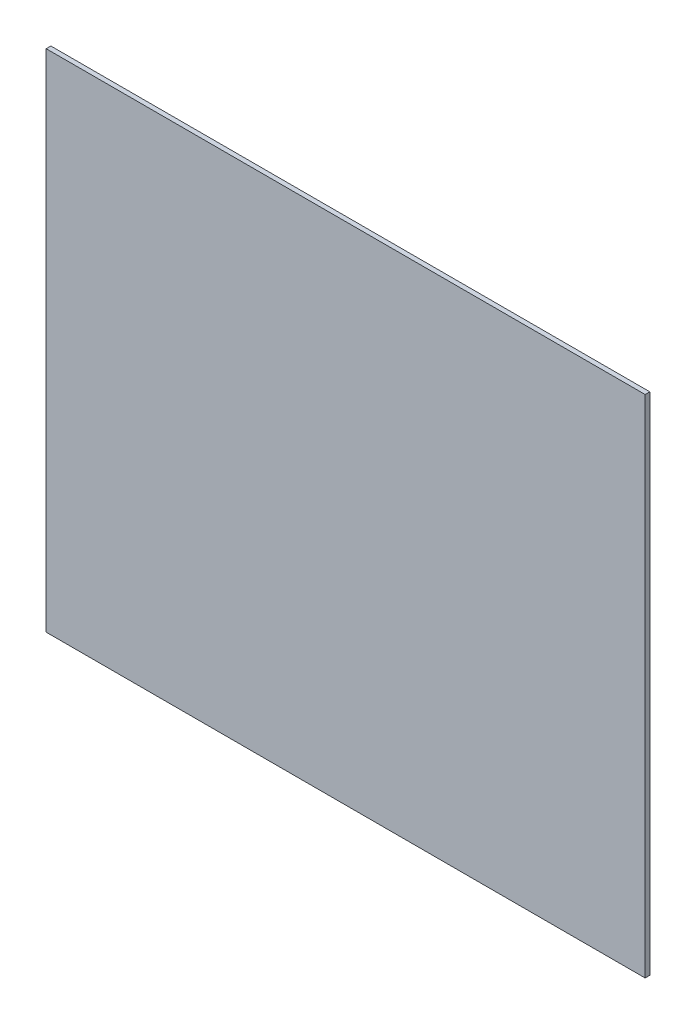
SolidWorks part; units mm, degrees
ref_plane "Plan de face" through (0, 0, 0) normal (0, 0, 1) x (1, 0, 0)
ref_plane "Plan de dessus" through (0, 0, 0) normal (0, 1, 0) x (1, 0, 0)
ref_plane "Plan de droite" through (0, 0, 0) normal (1, 0, 0) x (0, 0, -1)
sketch "Esquisse1" plane through (0, 0, 0) normal (0, 0, 1) x (1, 0, 0)
  line L1 (-416, -351) -> (416, -351)
  line L2 (-416, -351) -> (-416, 351)
  line L3 (-416, 351) -> (416, 351)
  line L4 (416, -351) -> (416, 351)
  line L5 (-416, -351) -> (416, 351) construction
  line L6 (-416, 351) -> (416, -351) construction
  point P0 (0, 0)
  dimension "D1" = 702
  dimension "D2" = 832
extrude "Boss.-Extru.1" add sketch "Esquisse1" along normal blind 6.5
